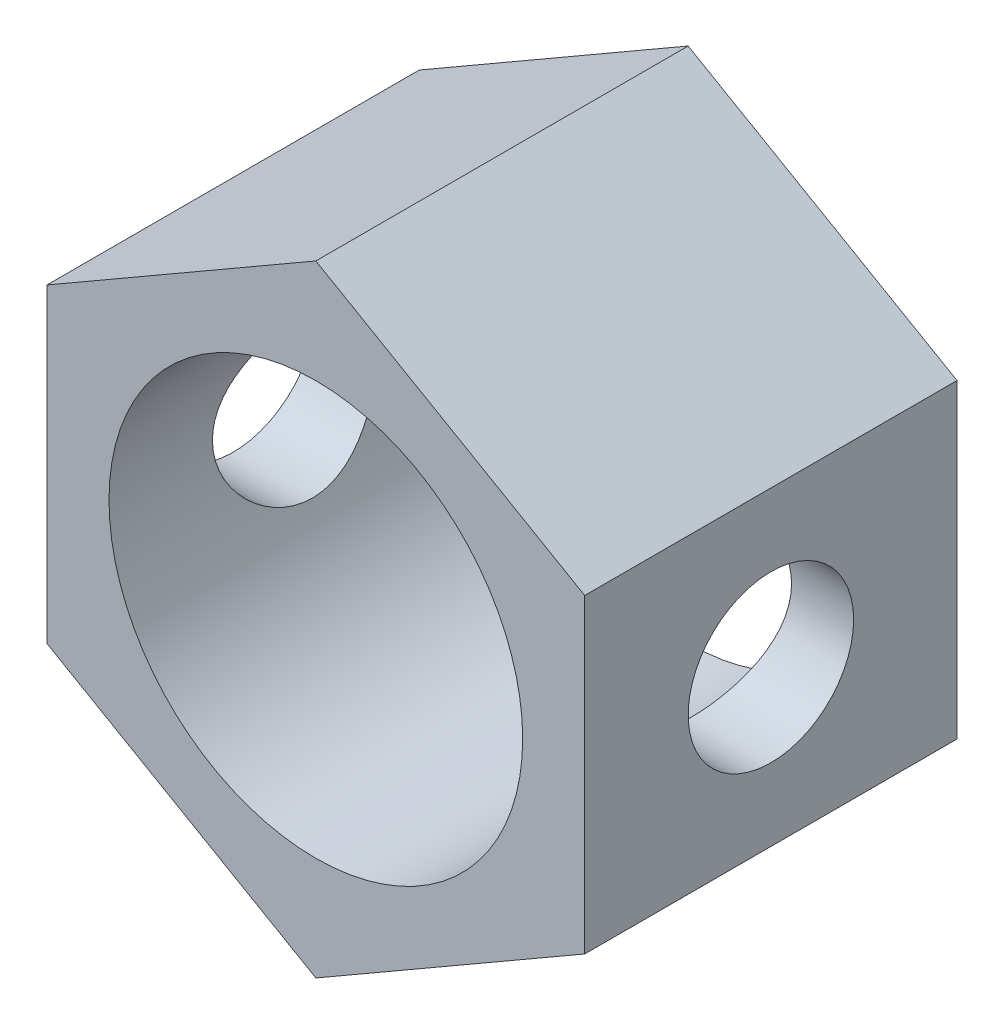
SolidWorks part; units mm, degrees
ref_plane "Front Plane" through (0, 0, 0) normal (0, 0, 1) x (1, 0, 0)
ref_plane "Top Plane" through (0, 0, 0) normal (0, 1, 0) x (1, 0, 0)
ref_plane "Right Plane" through (0, 0, 0) normal (1, 0, 0) x (0, 0, -1)
sketch "Sketch1" plane through (0, 0, 0) normal (0, 0, 1) x (1, 0, 0)
  line L0 (-4.3619, 16.0371) -> (-4.3619, 8.5315)
  line L1 (-17.3619, 16.0371) -> (-17.3619, 8.5315)
  line L2 (-4.3619, 16.0371) -> (-10.8619, 19.7898)
  line L3 (-10.8619, 19.7898) -> (-17.3619, 16.0371)
  line L4 (-17.3619, 8.5315) -> (-10.8619, 4.7787)
  line L5 (-10.8619, 4.7787) -> (-4.3619, 8.5315)
  circle A0 centre (-10.8619, 12.2843) radius 5
extrude "Boss-Extrude1" add sketch "Sketch1" along normal blind 9
sketch "Sketch2" plane through (-4.3619, 0, 0) normal (1, 0, 0) x (0, 0, -1)
  line L0 (-9, 12.2843) -> (0, 12.2843) construction
  line L1 (-9, 8.5315) -> (-9, 16.0371) construction
  line L2 (0, 8.5315) -> (0, 16.0371) construction
  circle A0 centre (-4.5, 12.2843) radius 2
extrude "Cut-Extrude1" cut sketch "Sketch2" against normal blind 20
